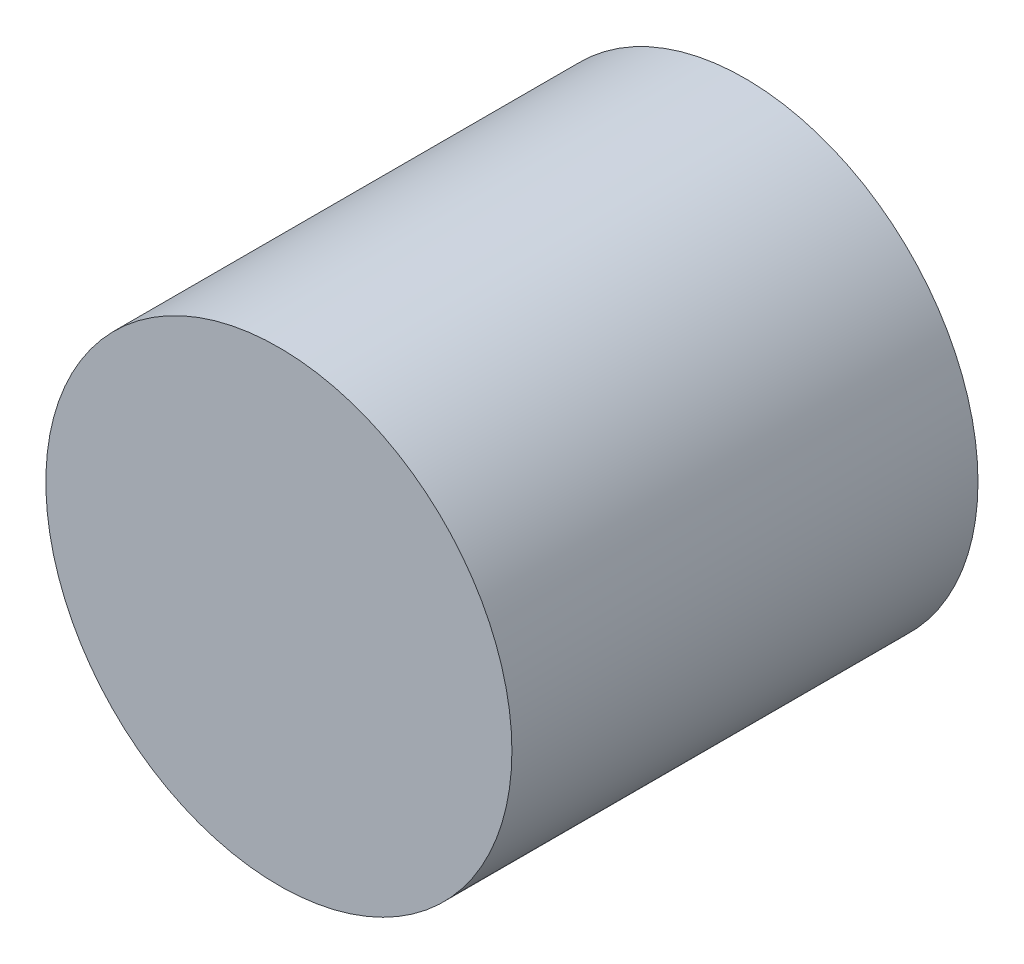
SolidWorks part; units mm, degrees
ref_plane "Front Plane" through (0, 0, 0) normal (0, 0, 1) x (1, 0, 0)
ref_plane "Top Plane" through (0, 0, 0) normal (0, 1, 0) x (1, 0, 0)
ref_plane "Right Plane" through (0, 0, 0) normal (1, 0, 0) x (0, 0, -1)
sketch "Sketch1" plane through (0, 0, 0) normal (0, 0, 1) x (1, 0, 0)
  circle A0 centre (0, 0) radius 35
  dimension "D1" = 70
extrude "Boss-Extrude1" add sketch "Sketch1" along normal blind 70
